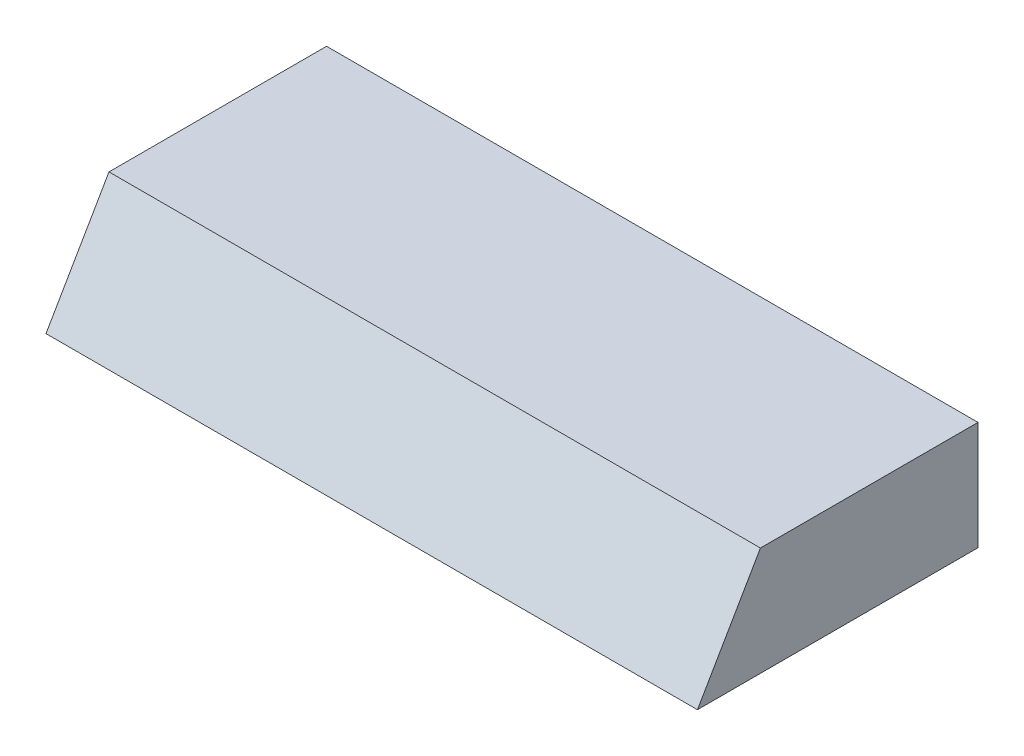
SolidWorks part; units mm, degrees
ref_plane "Front Plane" through (0, 0, 0) normal (0, 0, 1) x (1, 0, 0)
ref_plane "Top Plane" through (0, 0, 0) normal (0, 1, 0) x (1, 0, 0)
ref_plane "Right Plane" through (0, 0, 0) normal (1, 0, 0) x (0, 0, -1)
sketch "Sketch1" plane through (0, 0, 0) normal (0, 0, 1) x (1, 0, 0)
  line L1 (15, -2.5) -> (-15, -2.5)
  line L2 (15, -2.5) -> (15, 2.5)
  line L3 (15, 2.5) -> (-15, 2.5)
  line L4 (-15, -2.5) -> (-15, 2.5)
  line L5 (15, -2.5) -> (-15, 2.5) construction
  line L6 (15, 2.5) -> (-15, -2.5) construction
  point P0 (0, 0)
  dimension "D1" = 30
  dimension "D2" = 5
extrude "Boss-Extrude1" add sketch "Sketch1" along normal blind 12.92
sketch "Sketch2" plane through (15, 0, 0) normal (1, 0, 0) x (0, 0, -1)
  line L1 (-12.92, 2.5) -> (0, 2.5) construction
  line L2 (-10.02, 2.5) -> (-12.92, -2.5)
  line L3 (-12.92, -2.5) -> (-12.92, 2.5)
  line L4 (-12.92, 2.5) -> (-10.02, 2.5)
extrude "Cut-Extrude1" cut sketch "Sketch2" against normal blind 36
